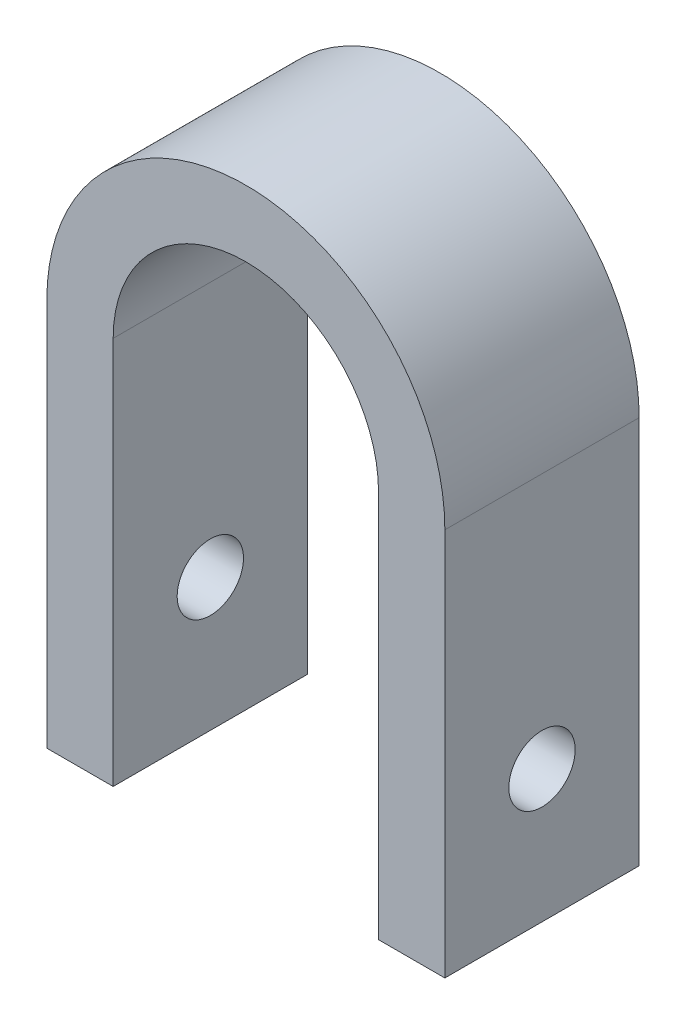
SolidWorks part; units mm, degrees
ref_plane "Front Plane" through (0, 0, 0) normal (0, 0, 1) x (1, 0, 0)
ref_plane "Top Plane" through (0, 0, 0) normal (0, 1, 0) x (1, 0, 0)
ref_plane "Right Plane" through (0, 0, 0) normal (1, 0, 0) x (0, 0, -1)
sketch "Sketch1" plane through (0, 0, 0) normal (0, 0, 1) x (1, 0, 0)
  line L0 (-4, 0) -> (-4, -11.7015)
  line L1 (-4, -5.7446) -> (-4, -25) construction
  line L3 (4, -21.6) -> (4, -5.7446) construction
  line L4 (-6, 0) -> (-6, -11.7015)
  line L5 (-6, -11.7015) -> (-4, -11.7015)
  line L6 (4, 0) -> (4, -11.7015)
  line L7 (6, 0) -> (6, -11.7015)
  line L8 (6, -11.7015) -> (4, -11.7015)
  arc A0 (4, 0) -> (-4, 0) centre (0, 0) ccw
  arc A1 (6, 0) -> (-6, 0) centre (0, 0) ccw
  dimension "D2" = 12
extrude "Boss-Extrude1" add sketch "Sketch1" along normal blind 5.8581
sketch "Sketch2" plane through (-6, 0, 0) normal (-1, 0, 0) x (0, 0, 1)
  line L0 (0, -11.7015) -> (2.9291, -7.7015) construction
  line L1 (2.9291, -7.7015) -> (5.8581, -11.7015) construction
  line L2 (5.8581, -11.7015) -> (0, -11.7015) construction
  circle A0 centre (2.9291, -7.7015) radius 1
  dimension "D2" = 2
  dimension "D1" = 4
extrude "Cut-Extrude1" cut sketch "Sketch2" against normal through all
